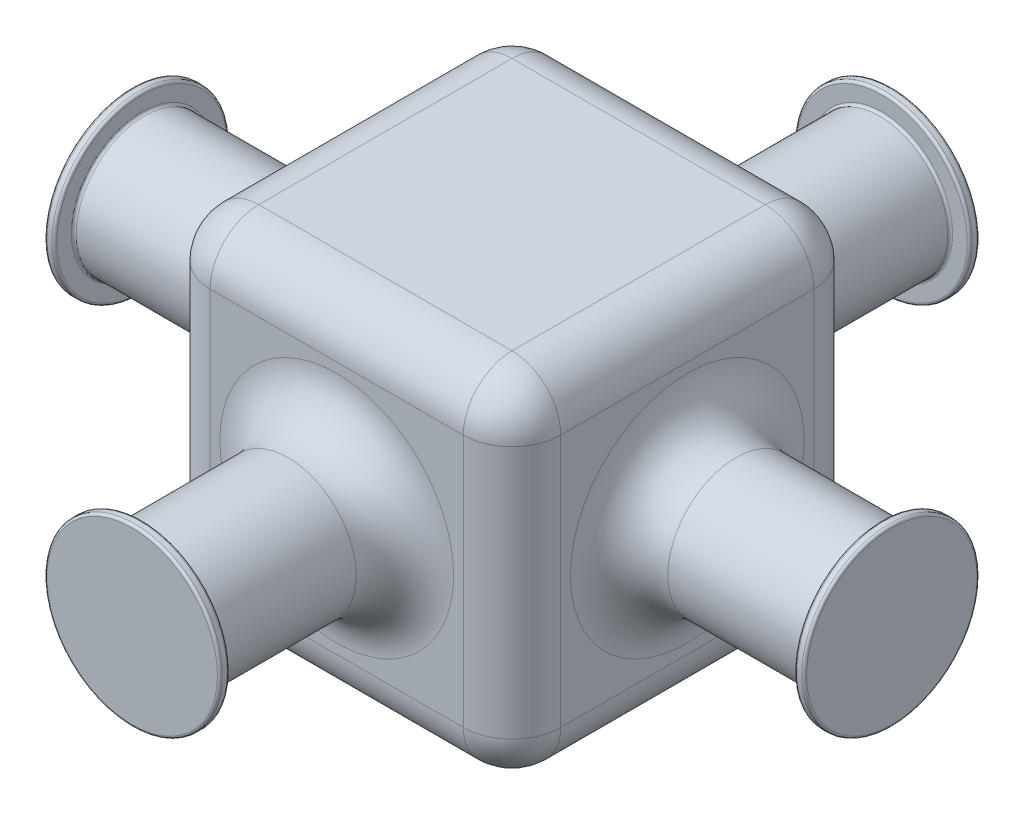
SolidWorks part; units mm, degrees
ref_plane "Front Plane" through (0, 0, 0) normal (0, 0, 1) x (1, 0, 0)
ref_plane "Top Plane" through (0, 0, 0) normal (0, 1, 0) x (1, 0, 0)
ref_plane "Right Plane" through (0, 0, 0) normal (1, 0, 0) x (0, 0, -1)
sketch "Sketch1" plane through (0, 0, 0) normal (0, 0, 1) x (1, 0, 0)
  line L5 (-18, -18) -> (18, -18)
  line L6 (-18, -18) -> (-18, 18)
  line L7 (-18, 18) -> (18, 18)
  line L8 (18, -18) -> (18, 18)
  line L9 (-18, -18) -> (18, 18) construction
  line L10 (-18, 18) -> (18, -18) construction
  point P0 (0, 0)
  dimension "D1" = 36
extrude "Boss-Extrude1" add sketch "Sketch1" along normal mid plane 36
sketch "Sketch3" plane through (0, 0, -18) normal (0, 0, -1) x (-1, 0, 0)
  circle A0 centre (0, 0) radius 7
  dimension "D1" = 14
extrude "Boss-Extrude2" add sketch "Sketch3" along normal blind 20
sketch "Sketch4" plane through (0, 0, -38) normal (0, 0, -1) x (-1, 0, 0)
  circle A0 centre (0, 0) radius 9
  circle A1 centre (0, 0) radius 7 construction
  dimension "D1" = 2
extrude "Boss-Extrude3" add sketch "Sketch4" along normal blind 1
fillet "Fillet1" radius 0.25 2 edges at (-9, 0, -38) (-9, 0, -39)
mirror "Mirror1" about plane through (0, 0, 0) normal (0, 0, 1) of "Boss-Extrude3", "Boss-Extrude2"
sketch "Sketch5" plane through (-18, 0, 0) normal (-1, 0, 0) x (0, 0, 1)
  circle A0 centre (0, 0) radius 7
  dimension "D1" = 14
extrude "Boss-Extrude4" add sketch "Sketch5" along normal blind 20
sketch "Sketch6" plane through (-38, 0, 0) normal (-1, 0, 0) x (0, 0, 1)
  circle A0 centre (0, 0) radius 9
  circle A1 centre (0, 0) radius 7 construction
  dimension "D1" = 2
extrude "Boss-Extrude5" add sketch "Sketch6" along normal blind 1
mirror "Mirror2" about plane through (0, 0, 0) normal (1, 0, 0) of "Boss-Extrude4", "Boss-Extrude5"
fillet "Fillet2" radius 0.25 4 edges at (39, 0, 9) (38, 0, 9) (-38, 0, 9) (-39, 0, 9)
fillet "Fillet3" radius 0.25 6 edges at (38, 0, 7) (-7, 0, 38) (-7, 0, -38) (-38, 0, 7) (-9, 0, 38) (-9, 0, 39)
fillet "Fillet4" radius 5 16 edges at (0, -18, -18) (-7, 0, -18) (-18, -18, 0) (-18, 0, -18) (-18, 0, 7) (-18, 18, 0) (0, 18, -18) (18, -18, 0) (18, 18, 0) (18, 0, -18) (18, 0, 7) (0, -18, 18) (-18, 0, 18) (0, 18, 18) (18, 0, 18) (-7, 0, 18)
